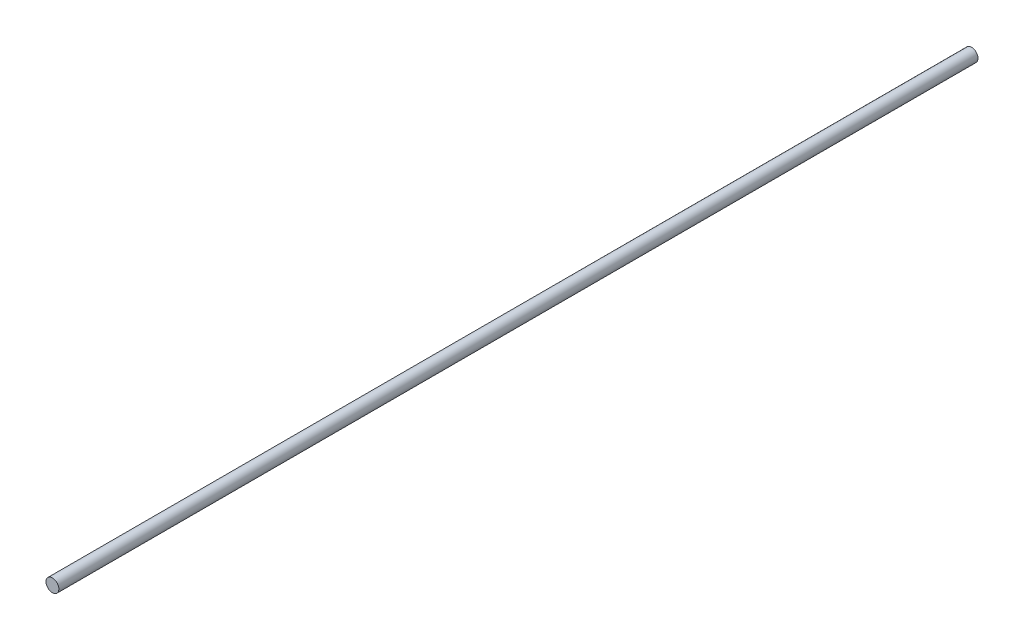
SolidWorks part; units mm, degrees
material "Hexcel AS4C (3000 filamentos)"
ref_plane "Alzado" through (0, 0, 0) normal (0, 0, 1) x (1, 0, 0)
ref_plane "Planta" through (0, 0, 0) normal (0, 1, 0) x (1, 0, 0)
ref_plane "Vista lateral" through (0, 0, 0) normal (1, 0, 0) x (0, 0, -1)
sketch "Croquis1" plane through (0, 0, 0) normal (0, 0, 1) x (1, 0, 0)
  circle A0 centre (0, 0) radius 3.5
  dimension "D1" = 7
extrude "Saliente-Extruir1" add sketch "Croquis1" along normal blind 500
